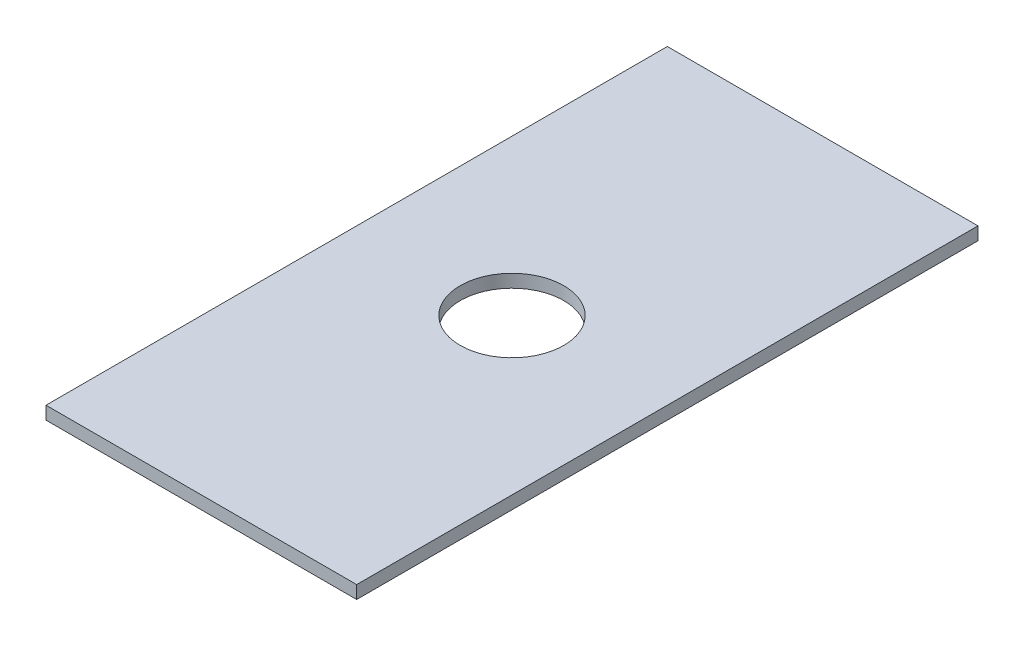
SolidWorks part; units mm, degrees
ref_plane "Front Plane" through (0, 0, 0) normal (0, 0, 1) x (1, 0, 0)
ref_plane "Top Plane" through (0, 0, 0) normal (0, 1, 0) x (1, 0, 0)
ref_plane "Right Plane" through (0, 0, 0) normal (1, 0, 0) x (0, 0, -1)
sketch "Sketch1" plane through (0, 0, 0) normal (0, 1, 0) x (1, 0, 0)
  line L1 (-38.1, -76.2) -> (38.1, -76.2)
  line L2 (-38.1, -76.2) -> (-38.1, 76.2)
  line L3 (-38.1, 76.2) -> (38.1, 76.2)
  line L4 (38.1, -76.2) -> (38.1, 76.2)
  line L5 (-38.1, -76.2) -> (38.1, 76.2) construction
  line L6 (-38.1, 76.2) -> (38.1, -76.2) construction
  circle A0 centre (0, 0) radius 12.7
  point P0 (0, 0)
extrude "Boss-Extrude1" add sketch "Sketch1" along normal blind 3.175
